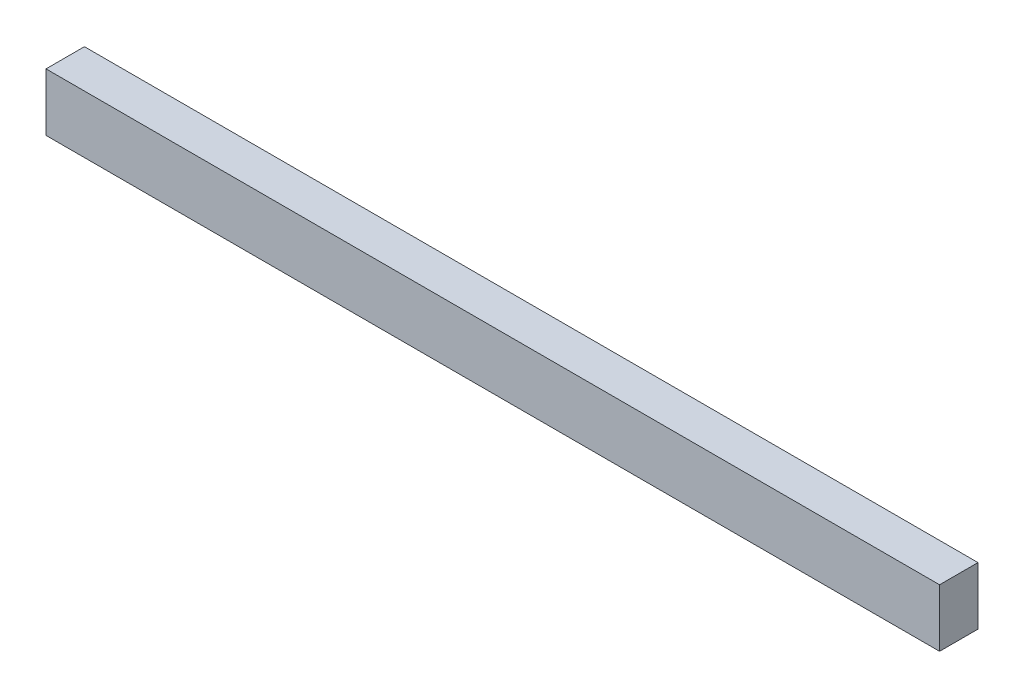
SolidWorks part; units mm, degrees
ref_plane "Front Plane" through (0, 0, 0) normal (0, 0, 1) x (1, 0, 0)
ref_plane "Top Plane" through (0, 0, 0) normal (0, 1, 0) x (1, 0, 0)
ref_plane "Right Plane" through (0, 0, 0) normal (1, 0, 0) x (0, 0, -1)
sketch "Sketch1" plane through (0, 0, 0) normal (0, 1, 0) x (1, 0, 0)
  line L1 (-295.275, -12.7) -> (295.275, -12.7)
  line L2 (-295.275, -12.7) -> (-295.275, 12.7)
  line L3 (-295.275, 12.7) -> (295.275, 12.7)
  line L4 (295.275, -12.7) -> (295.275, 12.7)
  line L5 (-295.275, -12.7) -> (295.275, 12.7) construction
  line L6 (-295.275, 12.7) -> (295.275, -12.7) construction
  point P0 (0, 0)
  dimension "D1" = 590.55
  dimension "D2" = 25.4
extrude "Boss-Extrude1" add sketch "Sketch1" along normal blind 38.1
sketch "Sketch6" plane through (0, 0, 0) normal (0, -1, 0) x (1, 0, 0)
  line L0 (-295.275, 12.7) -> (295.275, 12.7) construction
  line L1 (295.275, 12.7) -> (295.275, -12.7) construction
  point P0 (269.875, 6.35)
  point P3 (212.725, 6.35)
  point P6 (155.575, 6.35)
  point P7 (-142.875, 6.35)
  point P8 (98.425, 6.35)
  point P9 (41.275, 6.35)
  point P10 (-15.875, 6.35)
  point P11 (-200.025, 6.35)
  point P12 (-257.175, 6.35)
  point P13 (0, 0)
  point P14 (0, 0)
  dimension "D1" = 6.35
  dimension "D2" = 25.4
  dimension "D4" = 57.15
  dimension "D5" = 127
  dimension "D7" = 57.15
  dimension "D3" = 6
  dimension "D6" = 3
hole_wizard "#94 (0.3) Diameter Hole1" positions "Sketch6" profile "Sketch7" hole size "#94" standard "ANSI Inch"
sketch "Sketch7" plane through (269.875, 0, 6.35) normal (1, 0, 0) x (0, 0, -1)
  line L0 (0, 0) -> (0, 27.6893)
  line L1 (0, 27.6893) -> (3.81, 25.4)
  line L2 (3.81, 25.4) -> (3.81, 0)
  line L5 (3.81, 0) -> (0, 0)
  line L10 (0, 27.6893) -> (-3.81, 25.4) construction
  line L11 (0, -6.35) -> (0, 107.95) construction
  dimension "Hole Dia." = 7.62
  dimension "Hole Depth" = 25.4
  dimension "Drill Angle" = 118
